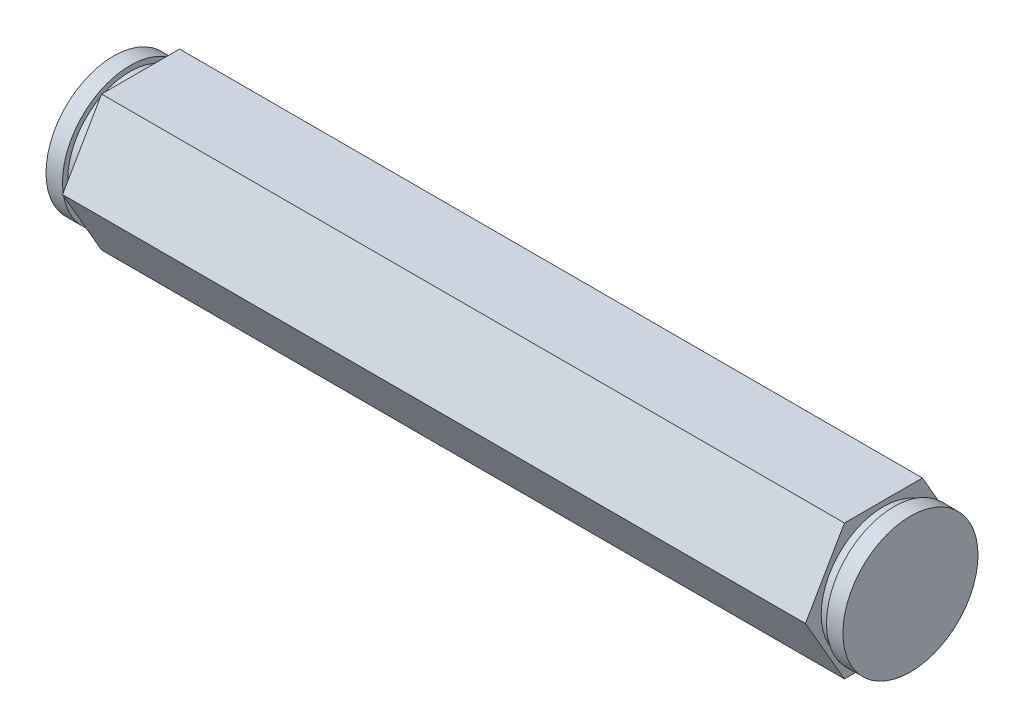
SolidWorks part; units mm, degrees
material "7075-T6 (SN)"
ref_plane "Front Plane" through (0, 0, 0) normal (0, 0, 1) x (1, 0, 0)
ref_plane "Top Plane" through (0, 0, 0) normal (0, 1, 0) x (1, 0, 0)
ref_plane "Right Plane" through (0, 0, 0) normal (1, 0, 0) x (0, 0, -1)
sketch "Sketch1" plane through (0, 0, 0) normal (1, 0, 0) x (0, 0, -1)
  line L1 (7.3323, 0) -> (3.6662, 6.35)
  line L2 (3.6662, 6.35) -> (-3.6662, 6.35)
  line L3 (-3.6662, 6.35) -> (-7.3323, 0)
  line L4 (-7.3323, 0) -> (-3.6662, -6.35)
  line L5 (-3.6662, -6.35) -> (3.6662, -6.35)
  line L6 (3.6662, -6.35) -> (7.3323, 0)
  circle A0 centre (0, 0) radius 6.35 construction
  dimension "D1" = 12.7
extrude "Boss-Extrude1" add sketch "Sketch1" along normal mid plane 74.93
sketch "Sketch2" plane through (0, 0, 0) normal (0, 1, 0) x (1, 0, 0)
  line L0 (34.925, -5.8547) -> (35.9156, -5.8547)
  line L1 (35.9156, -5.8547) -> (35.9156, -6.35)
  line L2 (35.9156, -6.35) -> (37.465, -6.35)
  line L3 (37.465, -6.35) -> (37.465, -8.89)
  line L4 (37.465, -8.89) -> (34.925, -8.89)
  line L5 (34.925, -8.89) -> (34.925, -5.8547)
  line L6 (0, 0) -> (49.5443, 0) construction
  dimension "D1" = 2.54
  dimension "D2" = 6.35
  dimension "D3" = 5.8547
  dimension "D4" = 2.54
  dimension "D5" = 0.9906
revolve "Cut-Revolve1" cut sketch "Sketch2" angle 360 about L6
mirror "Mirror1" about plane through (0, 0, 0) normal (1, 0, 0) of "Cut-Revolve1"
